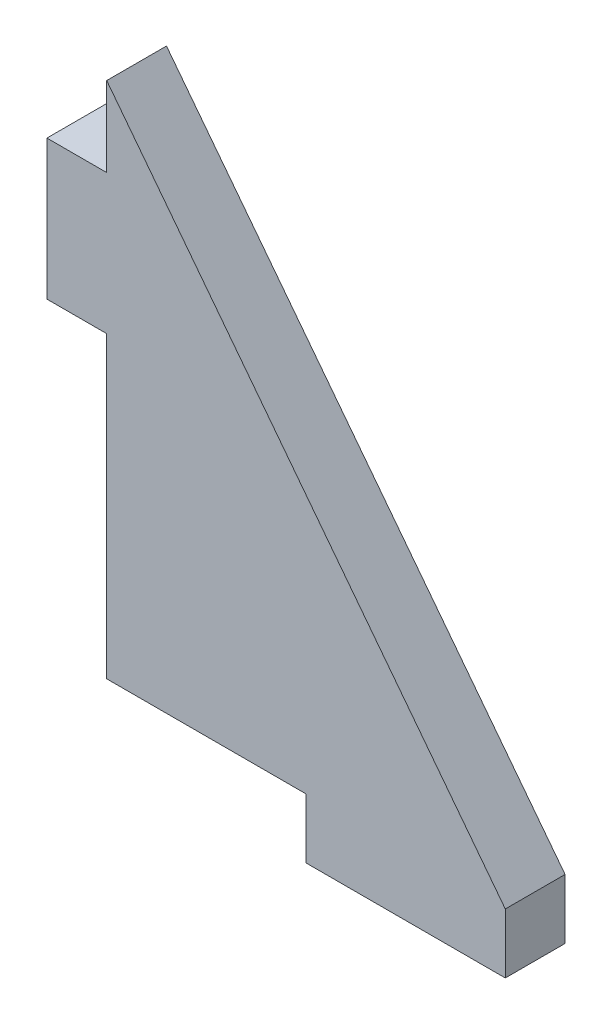
SolidWorks part; units mm, degrees
ref_plane "Alzado" through (0, 0, 0) normal (0, 0, 1) x (1, 0, 0)
ref_plane "Planta" through (0, 0, 0) normal (0, 1, 0) x (1, 0, 0)
ref_plane "Vista lateral" through (0, 0, 0) normal (1, 0, 0) x (0, 0, -1)
sketch "Croquis1" plane through (0, 0, 0) normal (0, 0, 1) x (1, 0, 0)
  line L0 (0, 0) -> (0, 26)
  line L1 (0, 26) -> (20, 0)
  line L2 (20, 0) -> (0, 0)
  line L4 (0, 22) -> (-3, 22)
  line L5 (0, 22) -> (0, 15)
  line L6 (0, 15) -> (-3, 15)
  line L7 (-3, 22) -> (-3, 15)
  line L8 (20, 0) -> (10, 0)
  line L9 (20, 0) -> (20, -3)
  line L10 (20, -3) -> (10, -3)
  line L11 (10, 0) -> (10, -3)
  dimension "D1" = 3
  dimension "D2" = 3
  dimension "D3" = 10
  dimension "D4" = 10
  dimension "D5" = 7
  dimension "D6" = 26
  dimension "D7" = 15
extrude "Saliente-Extruir1" add sketch "Croquis1" along normal blind 3 contours L2 L1 L0 | L4 L7 L6 L0 | L2 L11 L10 L9
